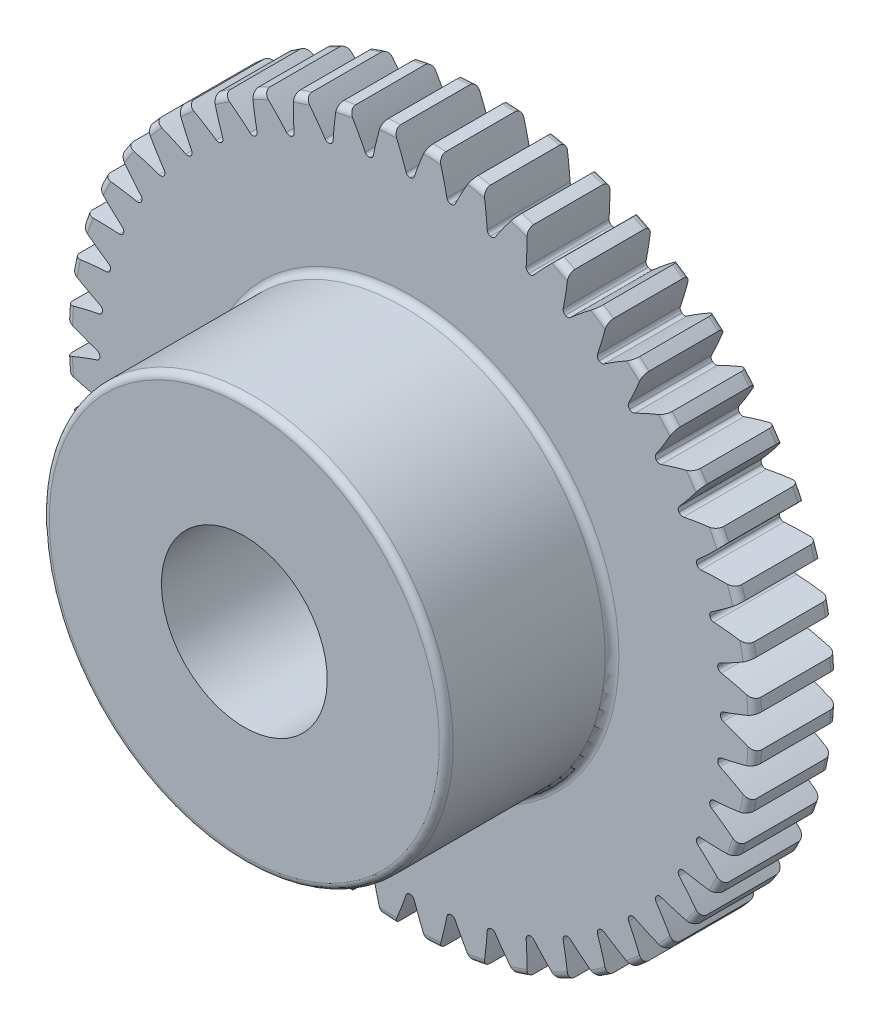
SolidWorks part; units mm, degrees
ref_plane "Front Plane" through (0, 0, 0) normal (0, 0, 1) x (1, 0, 0)
ref_plane "Top Plane" through (0, 0, 0) normal (0, 1, 0) x (1, 0, 0)
ref_plane "Right Plane" through (0, 0, 0) normal (1, 0, 0) x (0, 0, -1)
sketch "Sketch1" plane through (0, 0, 0) normal (0, 0, 1) x (1, 0, 0)
  line L0 (-609.6, 0) -> (609.6, 0) construction
  circle A0 centre (0, 0) radius 13.208 construction
  circle A1 centre (0, 0) radius 12.7 construction
  circle A2 centre (0, 0) radius 11.8851 construction
  circle A3 centre (0, 0) radius 7.7343 construction
  circle A4 centre (0, 0) radius 3.175 construction
  dimension "D2" = 0.508
  dimension "D3" = 1.3229
  dimension "D1" = 1.3229
sketch "Sketch2" plane through (0, 0, 0) normal (1, 0, 0) x (0, 0, -1)
  line L0 (0, 0) -> (-3.175, 0) construction
  line L1 (-3.175, 0) -> (-9.525, 0) construction
  dimension "Overall Width" = 9.525
  dimension "Face Width" = 3.175
sketch "Sketch4" plane through (0, 0, 0) normal (1, 0, 0) x (0, 0, -1)
  line L0 (-9.525, 3.175) -> (-9.525, 7.7343)
  line L1 (-9.525, 7.7343) -> (-3.175, 7.7343)
  line L2 (-3.175, 7.7343) -> (-3.175, 13.208)
  line L3 (-3.175, 13.208) -> (0, 13.208)
  line L4 (0, 13.208) -> (0, 3.175)
  line L5 (-3.175, 7.7343) -> (-3.175, 0) construction
  line L6 (0, 13.208) -> (0, -13.208) construction
  line L7 (-3.175, 7.7343) -> (0, 7.7343) construction
  line L12 (-9.525, 3.175) -> (0, 3.175)
revolve "Revolve1" add sketch "Sketch4" angle 360 about L1
fillet "Fillet2" radius 0.2642 4 edges at (0, 7.7343, 9.525) (0, 7.7343, 3.175) (0, 13.208, 3.175) (0, 13.208, 0)
sketch "Sketch7" plane through (0, 0, 3.175) normal (0, 0, 1) x (1, 0, 0)
  line L0 (0, 0) -> (0, 13.208) construction
  line L1 (0.4155, 12.6932) -> (0.6164, 13.1936) construction
  line L3 (0.8638, 13.1797) -> (0.8306, 12.6728) construction
  line L4 (0.8306, 12.6728) -> (0.7773, 11.8596) construction
  line L5 (0, 0) -> (0.7773, 11.8596) construction
  line L6 (0.4155, 12.6932) -> (0, 0) construction
  line L7 (0.4155, 12.6932) -> (0.4322, 13.2009) construction
  line L8 (0.4155, 12.6932) -> (0, 0) construction
  circle A0 centre (0, 0) radius 13.208 construction
  arc A1 (-0.0075, 11.8851) -> (0.0075, 11.8851) centre (0, 0) cw
  circle A2 centre (0, 0) radius 11.8851 construction
  arc A3 (-0.4155, 12.6932) -> (0.4155, 12.6932) centre (0, 0) cw construction
  circle A4 centre (0, 0) radius 12.7 construction
  arc A5 (1.0987, 13.1622) -> (0.6287, 13.193) centre (0, 0) ccw construction
  arc A6 (0.4155, 12.6932) -> (1.2448, 12.6388) centre (0, 0) cw construction
  arc A7 (-0.6287, 13.193) -> (0.6287, 13.193) centre (0, 0) cw
  arc A8 (0.1582, 11.9934) -> (0.6287, 13.193) centre (12.2011, 7.9614) cw
  arc A9 (-0.1582, 11.9934) -> (-0.6287, 13.193) centre (-12.2011, 7.9614) ccw
  arc A10 (-0.0075, 11.8851) -> (-0.1582, 11.9934) centre (-0.0076, 12.0438) cw
  arc A11 (0.0075, 11.8851) -> (0.1582, 11.9934) centre (0.0076, 12.0438) ccw
  point P26 (-0.1222, 11.8845)
  point P29 (0.1222, 11.8845)
  dimension "D4" = 0.1588
  dimension "D5" = 12.7
  dimension "D3" = 20
  dimension "D1" = 1.6624
  dimension "D2" = 0.8312
extrude "Cut-Extrude2" cut sketch "Sketch7" against normal through all
pattern_circular "CirPattern1" count 48 over 360 about axis through (0, 0, 0) along (0, 0, 1) of "Cut-Extrude2"
equation "\"D1@Sketch1\"=2.5*(\"Pitch Dia.@Sketch1\"/\"Number of Teeth@Sketch1\")"
equation "\"D1@CirPattern1\"=\"Number of Teeth@Sketch1\""
equation "\"D1@Fillet2\"=\"OD@Sketch1\"*.01"
equation "\"D1@Sketch7\"=3.14159*(\"Pitch Dia.@Sketch1\"/\"Number of Teeth@Sketch1\")"
equation "\"D2@Sketch7\"=\"D1@Sketch7\"/2"
equation "\"D4@Sketch7\"=\"D1@Sketch7\"*.0955"
equation "\"D5@Sketch7\"=\"Pitch Dia.@Sketch1\"/2"
